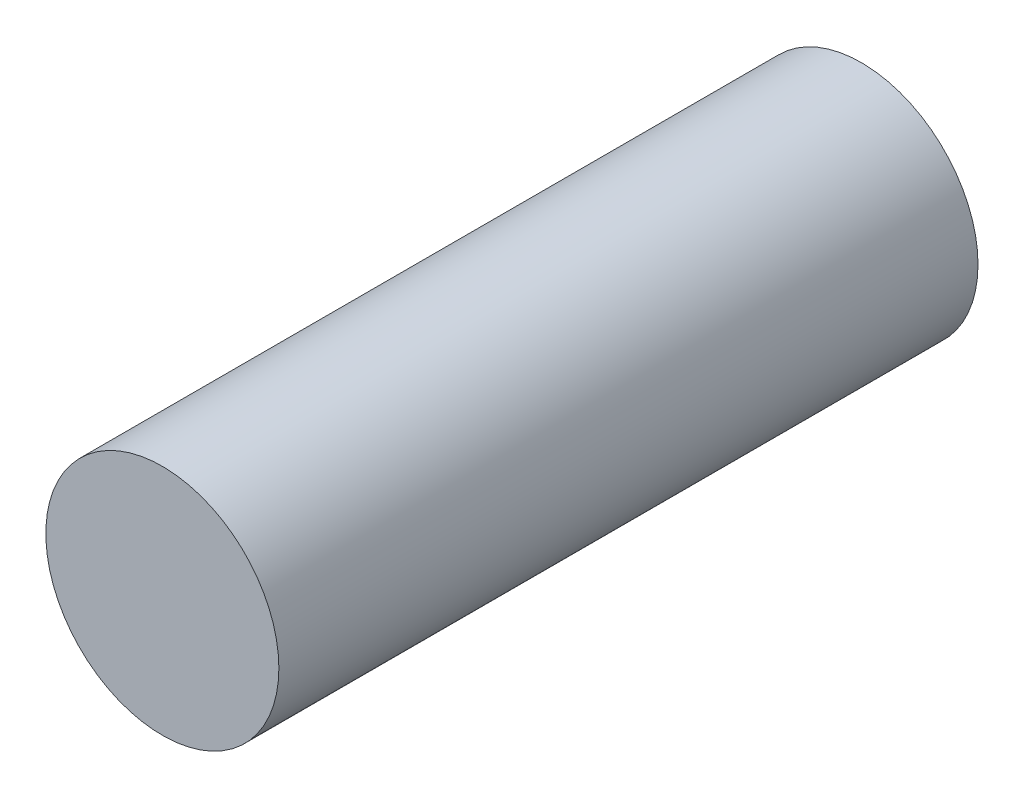
SolidWorks part; units mm, degrees
ref_plane "Front Plane" through (0, 0, 0) normal (0, 0, 1) x (1, 0, 0)
ref_plane "Top Plane" through (0, 0, 0) normal (0, 1, 0) x (1, 0, 0)
ref_plane "Right Plane" through (0, 0, 0) normal (1, 0, 0) x (0, 0, -1)
sketch "Sketch1" plane through (0, 0, 0) normal (0, 0, 1) x (1, 0, 0)
  circle A0 centre (0, 0) radius 5
  dimension "D1" = 10
extrude "Boss-Extrude1" add sketch "Sketch1" along normal blind 30
sketch "Sketch2" plane through (0, 0, 0) normal (0, 0, -1) x (-1, 0, 0)
  circle A0 centre (0, 0) radius 1.75
  dimension "D1" = 3.5
extrude "Cut-Extrude1" cut sketch "Sketch2" against normal blind 1
